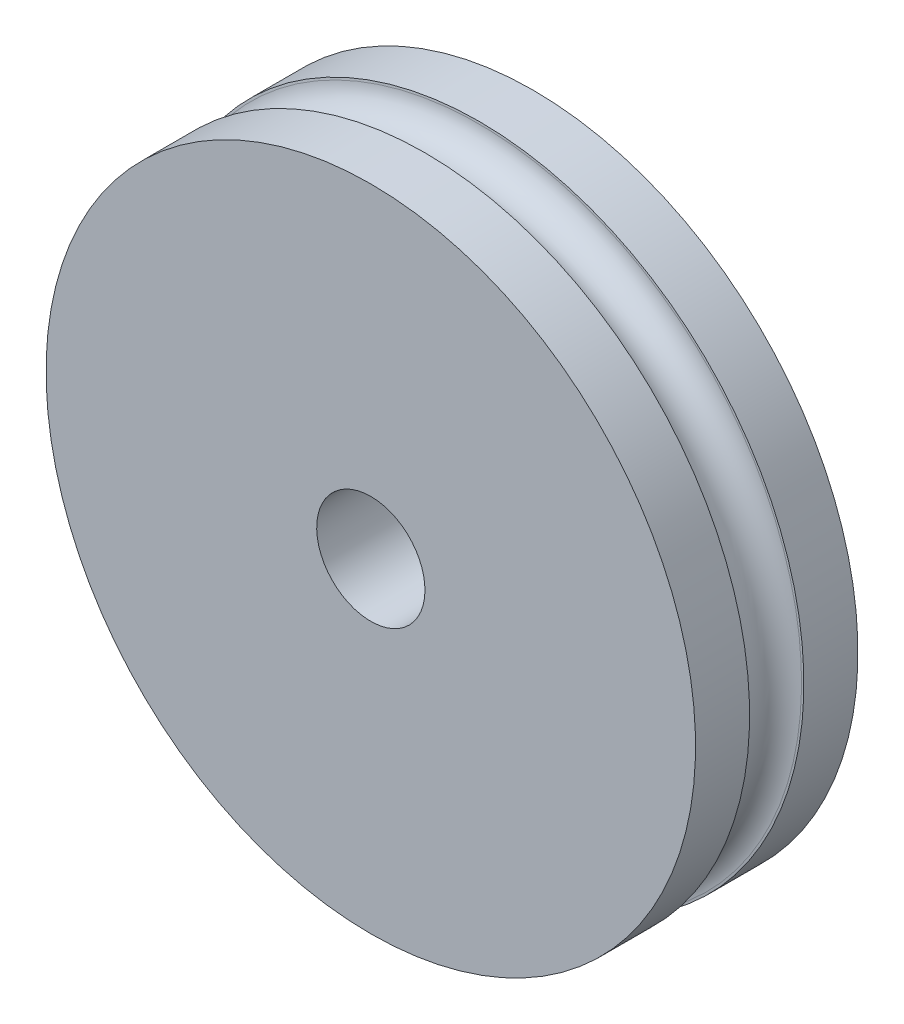
SolidWorks part; units mm, degrees
ref_plane "Front Plane" through (0, 0, 0) normal (0, 0, 1) x (1, 0, 0)
ref_plane "Top Plane" through (0, 0, 0) normal (0, 1, 0) x (1, 0, 0)
ref_plane "Right Plane" through (0, 0, 0) normal (1, 0, 0) x (0, 0, -1)
sketch "Sketch1" plane through (0, 0, 0) normal (1, 0, 0) x (0, 0, -1)
  line L0 (-4.7625, 0) -> (4.7625, 0) construction
  line L1 (-1.5925, 19.05) -> (1.5925, 19.05) construction
  line L2 (1.5925, 19.05) -> (4.7625, 19.05)
  line L5 (-4.7625, 19.05) -> (1.5925, 19.05) construction
  line L7 (-1.5925, 19.05) -> (-1.5815, 18.9243)
  line L13 (1.5815, 18.9243) -> (1.5925, 19.05)
  line L16 (4.7625, 3.175) -> (-4.7625, 3.175) construction
  line L17 (0, 19.05) -> (0, 0) construction
  line L18 (-1.5925, 19.05) -> (-4.7625, 19.05)
  line L22 (1.4536, 17.4625) -> (-1.4536, 17.4625) construction
  line L32 (-4.7625, 0) -> (-4.7625, 19.05)
  line L33 (4.7625, 19.05) -> (4.7625, 0)
  line L34 (-4.7625, 0) -> (4.7625, 0)
  circle A0 centre (0, 19.0627) radius 1.5875 construction
  arc A1 (-1.5815, 18.9243) -> (1.5815, 18.9243) centre (0, 19.0627) ccw
  point P16 (0, 17.4752)
  dimension "D1" = 10
  dimension "Belt Dia." = 3.175
  dimension "OD" = 38.1
  dimension "Bore" = 6.35
  dimension "Width" = 9.525
  dimension "PD" = 34.925
  dimension "Depth" = 1.5748
revolve "Revolve1" add sketch "Sketch1" angle 360 about L0
sketch "Sketch2" plane through (0, 0, -4.7625) normal (0, 0, -1) x (-1, 0, 0)
  circle A0 centre (0, 0) radius 3.175
  circle A1 centre (0, 0) radius 17.4625 construction
  point P4 (0, 3.175)
extrude "Cut-Extrude1" cut sketch "Sketch2" against normal up to vertex (9.525 mm away) up to point (0, 0, 4.7625)
